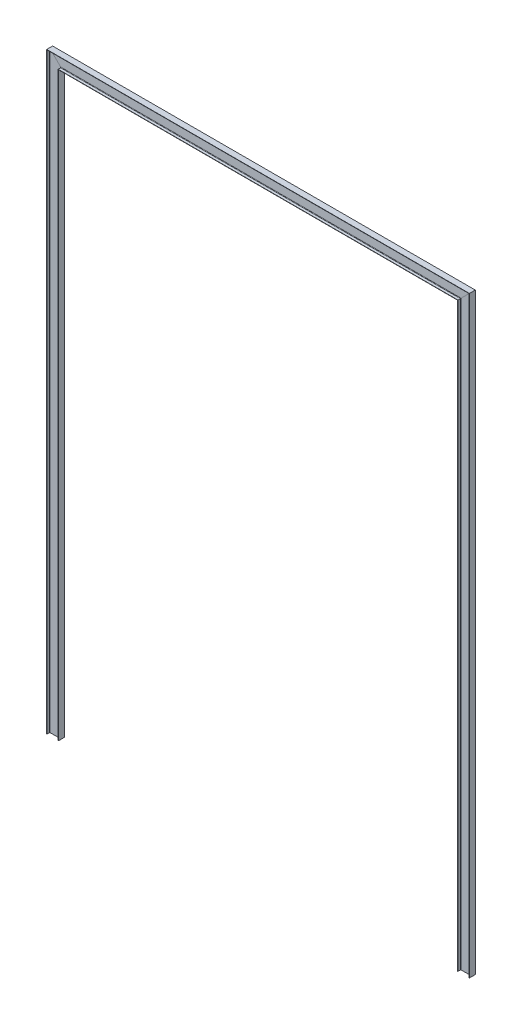
SolidWorks part; units mm, degrees
material "ASTM A36 Steel"
ref_plane "Front Plane" through (0, 0, 0) normal (0, 0, 1) x (1, 0, 0)
ref_plane "Top Plane" through (0, 0, 0) normal (0, 1, 0) x (1, 0, 0)
ref_plane "Right Plane" through (0, 0, 0) normal (1, 0, 0) x (0, 0, -1)
sketch "Sketch1" plane through (0, 0, 0) normal (0, 0, 1) x (1, 0, 0)
  line L0 (0, 0) -> (0, 10000)
  line L1 (0, 10000) -> (7000, 10000)
  line L2 (7000, 10000) -> (7000, 0)
  dimension "D1" = 10000
  dimension "D2" = 7000
other "W section W8X10(1)"
ref_plane "Plane1" through (0, 0, 0) normal (0, 1, 0) x (0, 0, 1)
sketch "Sketch11" plane through (0, 0, 0) normal (0, 1, 0) x (0, 0, 1)
  line L0 (-50.038, -100.203) -> (-50.038, -94.996)
  line L1 (-50.038, -94.996) -> (-9.779, -94.996)
  line L2 (-2.159, -87.376) -> (-2.159, 87.376)
  line L3 (-9.779, 94.996) -> (-50.038, 94.996)
  line L4 (-50.038, 94.996) -> (-50.038, 100.203)
  line L5 (-50.038, 100.203) -> (50.038, 100.203)
  line L6 (50.038, 100.203) -> (50.038, 94.996)
  line L7 (50.038, 94.996) -> (9.779, 94.996)
  line L8 (2.159, 87.376) -> (2.159, -87.376)
  line L9 (9.779, -94.996) -> (50.038, -94.996)
  line L10 (50.038, -94.996) -> (50.038, -100.203)
  line L11 (50.038, -100.203) -> (-50.038, -100.203)
  line L12 (0, 0) -> (0, 100.203) construction
  line L13 (-2.159, 0) -> (2.159, 0) construction
  arc A0 (-9.779, -94.996) -> (-2.159, -87.376) centre (-9.779, -87.376) ccw
  arc A1 (-2.159, 87.376) -> (-9.779, 94.996) centre (-9.779, 87.376) ccw
  arc A2 (9.779, 94.996) -> (2.159, 87.376) centre (9.779, 87.376) ccw
  arc A3 (2.159, -87.376) -> (9.779, -94.996) centre (9.779, -87.376) ccw
  point P23 (-50.038, 0)
  point P26 (0, -100.203)
  point P27 (50.038, 0)
  point P28 (0, 0)
  dimension "Ri" = 7.62
  dimension "D1" = 2.159
  dimension "D2" = 5.207
  dimension "Tw" = 4.318
  dimension "Bf" = 100.076
  dimension "Depth" = 200.406
  dimension "Tf" = 5.207
ref_point "Point1"
